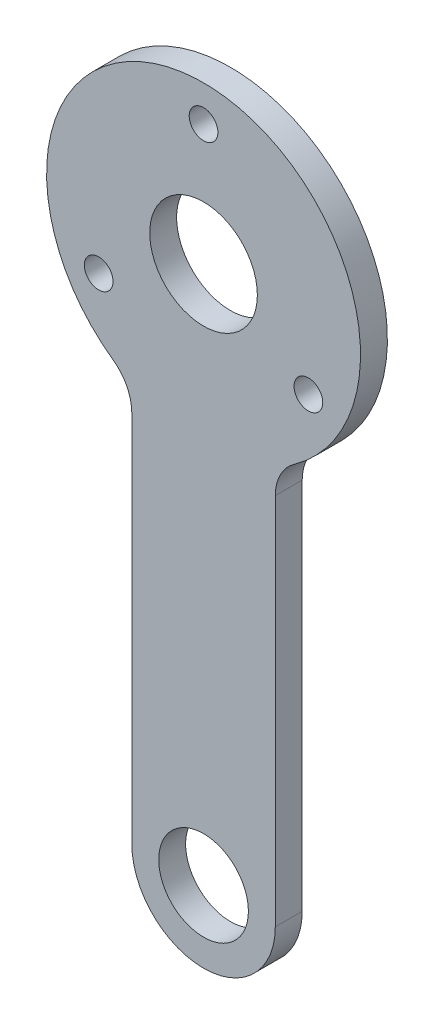
SolidWorks part; units mm, degrees
material "Thornel Mat VMA"
ref_plane "前视基准面" through (0, 0, 0) normal (0, 0, 1) x (1, 0, 0)
ref_plane "上视基准面" through (0, 0, 0) normal (0, 1, 0) x (1, 0, 0)
ref_plane "右视基准面" through (0, 0, 0) normal (1, 0, 0) x (0, 0, -1)
sketch "草图1" plane through (0, 0, 0) normal (0, 0, 1) x (1, 0, 0)
  line L0 (0, 0) -> (0, -60) construction
  line L1 (-8, -60) -> (-8, -18.3644)
  line L2 (8, -60) -> (8, -18.3644)
  circle A0 centre (0, 0) radius 13.5 construction
  circle A1 centre (0, 13.5) radius 1.6
  circle A2 centre (11.6913, -6.75) radius 1.6
  circle A3 centre (-11.6913, -6.75) radius 1.6
  circle A4 centre (0, 0) radius 6
  arc A5 (10.1111, -14.2834) -> (-10.1111, -14.2834) centre (0, 0) ccw
  circle A6 centre (0, -60) radius 5
  arc A7 (-8, -60) -> (8, -60) centre (0, -60) ccw
  arc A8 (8, -18.3644) -> (10.1111, -14.2834) centre (13, -18.3644) cw
  arc A9 (-8, -18.3644) -> (-10.1111, -14.2834) centre (-13, -18.3644) ccw
  point P11 (0, 0)
  dimension "D1" = 27
  dimension "D2" = 3.2
  dimension "D4" = 12
  dimension "D5" = 35
  dimension "D7" = 10
  dimension "D8" = 16
  dimension "D9" = 5
  dimension "D6" = 60
  dimension "D3" = 3
extrude "凸台-拉伸1" add sketch "草图1" along normal blind 3
